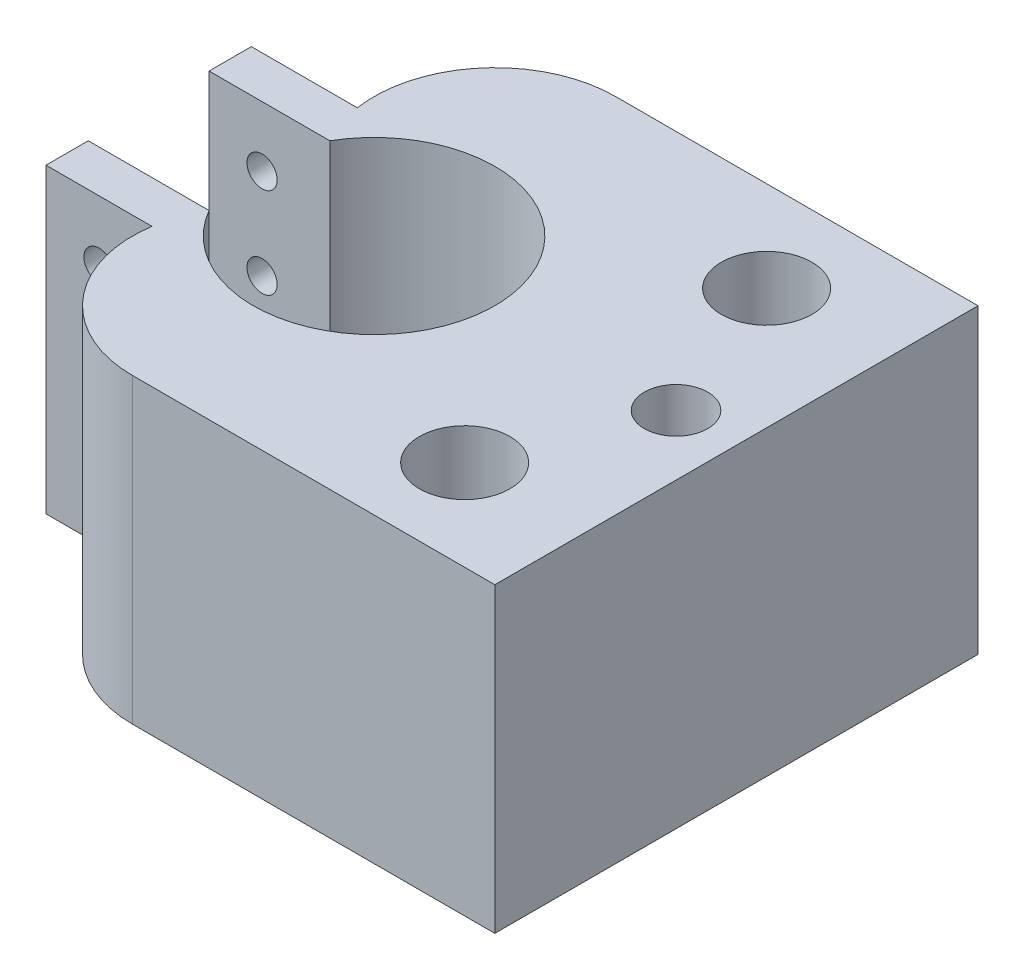
SolidWorks part; units mm, degrees
ref_plane "Front Plane" through (0, 0, 0) normal (0, 0, 1) x (1, 0, 0)
ref_plane "Top Plane" through (0, 0, 0) normal (0, 1, 0) x (1, 0, 0)
ref_plane "Right Plane" through (0, 0, 0) normal (1, 0, 0) x (0, 0, -1)
sketch "Sketch1" plane through (0, 0, 0) normal (0, 1, 0) x (1, 0, 0)
  line L0 (17.8229, 18.6459) -> (40, 40.8229) construction
  line L1 (-20, 40.8229) -> (40, 40.8229)
  line L3 (-20, -39.1771) -> (40, -39.1771)
  line L4 (40, 40.8229) -> (40, -39.1771)
  line L5 (-57.3205, -9.1771) -> (-37.3205, -9.1771)
  line L6 (-57.3205, 17.8229) -> (-39.7737, 17.8229)
  line L7 (17.8229, -17) -> (40, -39.1771) construction
  line L8 (24.75, 0.8229) -> (121.2722, 0.8229) construction
  line L9 (-57.3205, 17.8229) -> (-57.3205, 10.8229)
  line L10 (-57.3205, 10.8229) -> (-37.3205, 10.8229)
  line L12 (-57.3205, -16.1771) -> (-57.3205, -9.1771)
  line L13 (-57.3205, -16.1771) -> (-39.7737, -16.1771)
  circle A0 centre (20, 25.8229) radius 7.5
  circle A1 centre (20, -24.1771) radius 7.5
  circle A2 centre (30, 0.8229) radius 5.25
  arc A3 (-37.3205, -9.1771) -> (-37.3205, 10.8229) centre (-20, 0.8229) ccw
  arc A4 (-20, 40.8229) -> (-39.7737, 17.8229) centre (-20, 20.8229) ccw
  arc A6 (-39.7737, -16.1771) -> (-20, -39.1771) centre (-20, -19.1771) ccw
  point P0 (0, 0)
  dimension "D5" = 15
  dimension "D6" = 10.5
  dimension "D9" = 40
  dimension "D10" = 40
  dimension "D1" = 15
  dimension "D2" = 20
  dimension "D4" = 7
  dimension "D7" = 40
  dimension "D8" = 10
extrude "Boss-Extrude1" add sketch "Sketch1" along normal blind 50
sketch "Sketch2" plane through (0, 0, 16.1771) normal (0, 0, 1) x (1, 0, 0)
  line L0 (-48.5471, 50) -> (-48.5471, 0) construction
  line L1 (-57.3205, 50) -> (-39.7737, 50) construction
  line L2 (-57.3205, 0) -> (-39.7737, 0) construction
  circle A0 centre (-48.5471, 40) radius 2.5
  circle A1 centre (-48.5471, 25) radius 2.5
  circle A2 centre (-48.5471, 10) radius 2.5
  dimension "D2" = 5
  dimension "D3" = 5
  dimension "D4" = 5
  dimension "D1" = 50
  dimension "D5" = 15
  dimension "D6" = 15
extrude "Cut-Extrude1" cut sketch "Sketch2" against normal blind 50
